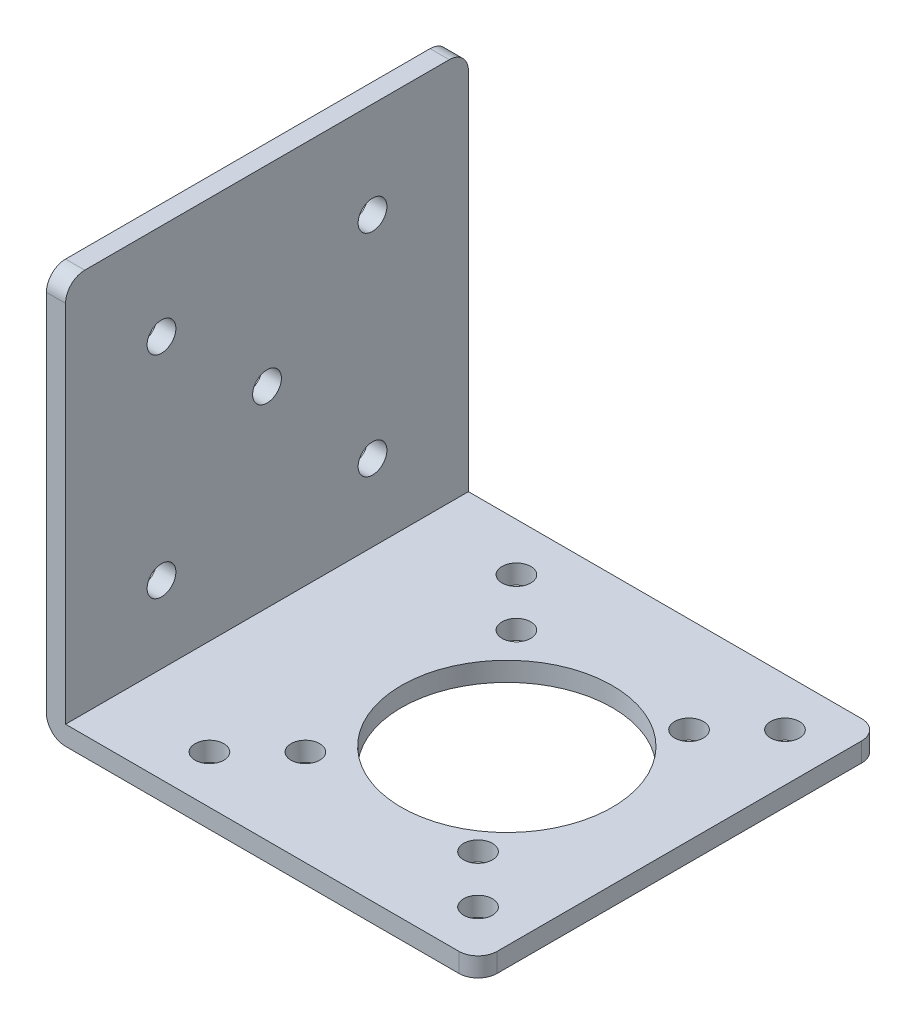
SolidWorks part; units mm, degrees
ref_plane "Front Plane" through (0, 0, 0) normal (0, 0, 1) x (1, 0, 0)
ref_plane "Top Plane" through (0, 0, 0) normal (0, 1, 0) x (1, 0, 0)
ref_plane "Right Plane" through (0, 0, 0) normal (1, 0, 0) x (0, 0, -1)
sketch "Sketch1" plane through (0, 0, 0) normal (0, 0, 1) x (1, 0, 0)
  line L0 (0, 0) -> (45, 0)
  line L1 (45, 0) -> (45, 2)
  line L2 (45, 2) -> (2, 2)
  line L3 (2, 2) -> (2, 42)
  line L4 (2, 42) -> (0, 42)
  line L5 (0, 42) -> (0, 0)
  dimension "D1" = 45
  dimension "D2" = 2
  dimension "D3" = 2
  dimension "D4" = 42
extrude "Boss-Extrude1" add sketch "Sketch1" against normal blind 42
fillet "Fillet1" radius 2 1 edges at (0, 0, -21)
fillet "Fillet2" radius 2 4 edges at (45, 1, -42) (45, 1, 0) (1, 42, -42) (1, 42, 0)
ref_plane "Plane1" through (0, 2, 0) normal (0, 1, 0) x (1, 0, 0)
sketch "Sketch3" plane through (0, 2, 0) normal (0, 1, 0) x (1, 0, 0)
  line L0 (2, 21) -> (12, 21) construction
  line L2 (43, 42) -> (2, 42) construction
  line L3 (45, 40) -> (45, 2) construction
  line L4 (43, 0) -> (2, 0) construction
  line L5 (2, 42) -> (2, 0) construction
  line L6 (12, 21) -> (12, 0) construction
  line L7 (12, 0) -> (12, 42) construction
  circle A0 centre (27, 21) radius 11
  circle A1 centre (40, 37) radius 1.5
  circle A2 centre (40, 5) radius 1.5
  circle A3 centre (35, 32) radius 1.5
  circle A4 centre (35, 10) radius 1.5
  circle A5 centre (17, 10) radius 1.5
  circle A6 centre (17, 32) radius 1.5
  circle A7 centre (12, 37) radius 1.5
  circle A8 centre (12, 5) radius 1.5
  dimension "D2" = 22
  dimension "D3" = 3
  dimension "D8" = 3
  dimension "D11" = 10
  dimension "D4" = 5
  dimension "D5" = 5
  dimension "D6" = 5
  dimension "D7" = 5
  dimension "D9" = 10
  dimension "D10" = 10
  dimension "D12" = 10
  dimension "D13" = 10
  dimension "D14" = 10
  dimension "D15" = 5
  dimension "D16" = 5
  dimension "D17" = 25
extrude "Cut-Extrude1" cut sketch "Sketch3" against normal up to next
ref_plane "Plane2" through (2, 0, 0) normal (1, 0, 0) x (0, 0, -1)
sketch "Sketch4" plane through (2, 0, 0) normal (1, 0, 0) x (0, 0, -1)
  line L0 (0, 2) -> (0, 40) construction
  line L3 (40, 42) -> (2, 42) construction
  line L4 (40, 0) -> (2, 0) construction
  line L5 (42, 2) -> (42, 40) construction
  circle A0 centre (21, 22) radius 1.5
  circle A1 centre (10, 32) radius 1.5
  circle A2 centre (32, 32) radius 1.5
  circle A3 centre (10, 10) radius 1.5
  circle A4 centre (32, 10) radius 1.5
  dimension "D1" = 3
  dimension "D3" = 10
  dimension "D6" = 10
  dimension "D7" = 10
  dimension "D8" = 10
  dimension "D2" = 10
  dimension "D4" = 10
  dimension "D5" = 10
  dimension "D9" = 10
extrude "Cut-Extrude2" cut sketch "Sketch4" against normal up to next
